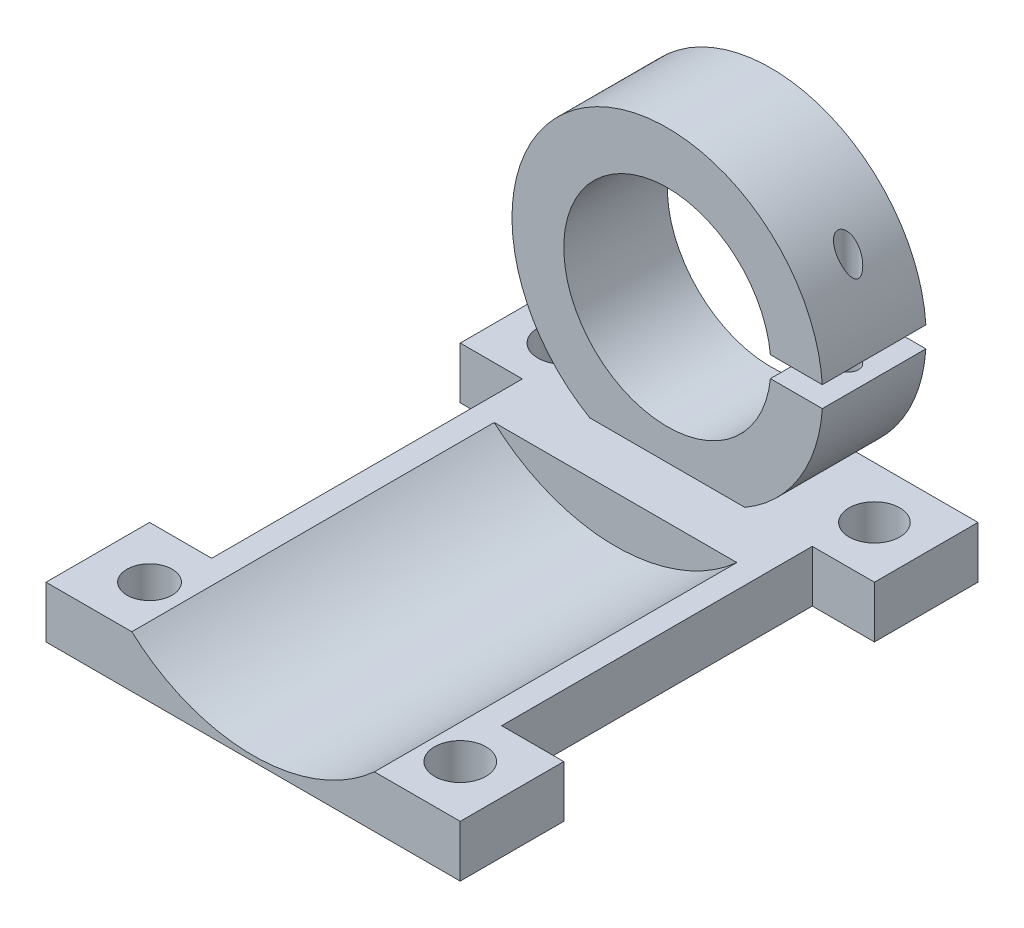
SolidWorks part; units mm, degrees
ref_plane "Front Plane" through (0, 0, 0) normal (0, 0, 1) x (1, 0, 0)
ref_plane "Top Plane" through (0, 0, 0) normal (0, 1, 0) x (1, 0, 0)
ref_plane "Right Plane" through (0, 0, 0) normal (1, 0, 0) x (0, 0, -1)
sketch "Sketch1" plane through (0, 0, 0) normal (0, 1, 0) x (1, 0, 0)
  line L1 (14, -25) -> (-14, -25)
  line L2 (14, -25) -> (14, 25)
  line L3 (14, 25) -> (-14, 25)
  line L4 (-14, -25) -> (-14, 25)
  line L5 (14, -25) -> (-14, 25) construction
  line L6 (14, 25) -> (-14, -25) construction
  line L7 (-14, -25) -> (-20, -25)
  line L8 (-14, -25) -> (-14, -15)
  line L9 (-14, -15) -> (-20, -15)
  line L10 (-20, -25) -> (-20, -15)
  line L11 (-14, 25) -> (-20, 25)
  line L12 (-14, 25) -> (-14, 15)
  line L13 (-14, 15) -> (-20, 15)
  line L14 (-20, 25) -> (-20, 15)
  line L15 (14, 25) -> (20, 25)
  line L16 (14, 25) -> (14, 15)
  line L17 (14, 15) -> (20, 15)
  line L18 (20, 25) -> (20, 15)
  line L19 (14, -25) -> (20, -25)
  line L20 (14, -25) -> (14, -15)
  line L21 (14, -15) -> (20, -15)
  line L22 (20, -25) -> (20, -15)
  point P0 (0, 0)
  dimension "D1" = 50
  dimension "D2" = 6
  dimension "D3" = 6
  dimension "D4" = 6
  dimension "D5" = 6
  dimension "D6" = 10
  dimension "D7" = 10
  dimension "D8" = 10
  dimension "D9" = 10
  dimension "D10" = 40
extrude "Boss-Extrude1" add sketch "Sketch1" along normal blind 5 contours L10 L7 L4 L9 | L4 L1 L2 L3 | L11 L14 L13 L4 | L18 L15 L2 L17 | L19 L22 L21 L2
sketch "Sketch2" plane through (0, 0, -25) normal (0, 0, -1) x (-1, 0, 0)
  line L0 (-9.9499, 19) -> (-14.9666, 19)
  line L1 (-9.9499, 17) -> (-14.9666, 17)
  arc A0 (-9.9499, 17) -> (-9.9499, 19) centre (0, 18) ccw
  arc A1 (-14.9666, 17) -> (-14.9666, 19) centre (0, 18) ccw
  dimension "D2" = 20
  dimension "D3" = 30
  dimension "D1" = 18
extrude "Boss-Extrude2" add sketch "Sketch2" against normal blind 10
sketch "Sketch4" plane through (0, 0, 25) normal (0, 0, 1) x (1, 0, 0)
  circle A0 centre (0, 18) radius 17.5
  dimension "D1" = 35
extrude "Cut-Extrude1" cut sketch "Sketch4" against normal blind 35
sketch "Sketch5" plane through (0, 5, 0) normal (0, 1, 0) x (1, 0, 0)
  line L0 (-20, -25) -> (-20, -15) construction
  line L2 (-11.7154, -25) -> (-20, -25) construction
  line L3 (20, -25) -> (20, -15) construction
  line L4 (20, 25) -> (20, 15) construction
  line L5 (-20, 25) -> (-20, 15) construction
  line L6 (-14, 15) -> (-20, 15) construction
  circle A0 centre (-15, -20) radius 2.18
  circle A1 centre (15, -20) radius 2.4822
  circle A2 centre (15, 20) radius 2.4462
  circle A3 centre (-15, 20) radius 2.5115
  dimension "D7" = 4.3599
  dimension "D1" = 5
  dimension "D2" = 5
  dimension "D3" = 5
  dimension "D4" = 5
  dimension "D5" = 5
  dimension "D6" = 5
sketch "Sketch6" plane through (0, 17, 0) normal (0, 1, 0) x (1, 0, 0)
  circle A0 centre (12.4583, 20) radius 1
  dimension "D1" = 2
extrude "Cut-Extrude2" cut sketch "Sketch6" along normal blind 30 and the other way blind 5
extrude "Cut-Extrude3" cut sketch "Sketch5" against normal blind 30
